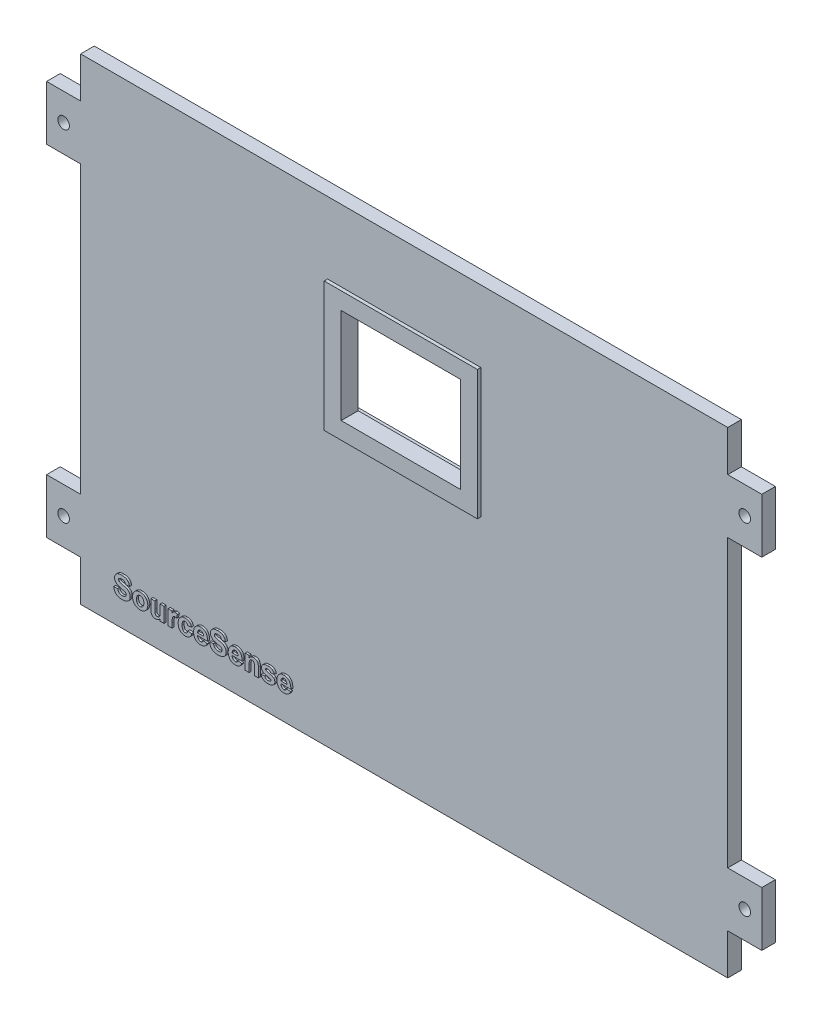
SolidWorks part; units mm, degrees
ref_plane "Front Plane" through (0, 0, 0) normal (0, 0, 1) x (1, 0, 0)
ref_plane "Top Plane" through (0, 0, 0) normal (0, 1, 0) x (1, 0, 0)
ref_plane "Right Plane" through (0, 0, 0) normal (1, 0, 0) x (0, 0, -1)
other "Configuration Table"
sketch "Sketch1" plane through (0, 0, 0) normal (0, 0, 1) x (1, 0, 0)
  line L0 (-95, -70) -> (95, -70)
  line L1 (95, -70) -> (95, 70)
  line L2 (95, 70) -> (-95, 70)
  line L3 (-95, 70) -> (-95, -70)
extrude "Lid_Plate" add sketch "Sketch1" along normal blind 4 from offset 44
sketch "Sketch2" plane through (0, 0, 0) normal (0, 0, 1) x (1, 0, 0)
  line L0 (-105, -58) -> (-95, -58)
  line L1 (-95, -58) -> (-95, -42)
  line L2 (-95, -42) -> (-105, -42)
  line L3 (-105, -42) -> (-105, -58)
  line L4 (-105, 42) -> (-95, 42)
  line L5 (-95, 42) -> (-95, 58)
  line L6 (-95, 58) -> (-105, 58)
  line L7 (-105, 58) -> (-105, 42)
  line L8 (95, -58) -> (105, -58)
  line L9 (105, -58) -> (105, -42)
  line L10 (105, -42) -> (95, -42)
  line L11 (95, -42) -> (95, -58)
  line L12 (95, 42) -> (105, 42)
  line L13 (105, 42) -> (105, 58)
  line L14 (105, 58) -> (95, 58)
  line L15 (95, 58) -> (95, 42)
extrude "Lid_Lugs" add sketch "Sketch2" along normal blind 4 from offset 44
sketch "Sketch3" plane through (0, 0, 0) normal (0, 0, 1) x (1, 0, 0)
  line L1 (-17.5, 16) -> (17.5, 16)
  line L2 (-17.5, 16) -> (-17.5, 44)
  line L3 (-17.5, 44) -> (17.5, 44)
  line L4 (17.5, 16) -> (17.5, 44)
  line L5 (-17.5, 16) -> (17.5, 44) construction
  line L6 (-17.5, 44) -> (17.5, 16) construction
  point P5 (0, 30)
  dimension "D1" = 35
  dimension "D2" = 28
extrude "TFT_Window" cut sketch "Sketch3" along normal through all and the other way through all
sketch "Sketch4" plane through (0, 0, 0) normal (0, 0, 1) x (1, 0, 0)
  line L0 (-22.5, 11) -> (22.5, 11)
  line L1 (22.5, 11) -> (22.5, 49)
  line L2 (22.5, 49) -> (-22.5, 49)
  line L3 (-22.5, 49) -> (-22.5, 11)
  line L4 (-17.5, 16) -> (17.5, 16)
  line L5 (17.5, 16) -> (17.5, 44)
  line L6 (17.5, 44) -> (-17.5, 44)
  line L7 (-17.5, 44) -> (-17.5, 16)
extrude "TFT_Bezel" add sketch "Sketch4" along normal blind 1 from offset 48
sketch "Sketch5" plane through (0, 0, 0) normal (0, 0, 1) x (1, 0, 0)
  circle A0 centre (-100, -50) radius 1.7
  circle A1 centre (-100, 50) radius 1.7
  circle A2 centre (100, -50) radius 1.7
  circle A3 centre (100, 50) radius 1.7
  dimension "D1" = 3.4
  dimension "D2" = 3.4
  dimension "D3" = 3.4
  dimension "D4" = 3.4
extrude "Lid_Screw_Holes_M3" cut sketch "Sketch5" along normal through all and the other way through all
sketch "Sketch6" plane through (0, 0, 0) normal (0, 0, 1) x (1, 0, 0)
  line L0 (-25, 10.2) -> (25, 10.2)
  line L1 (25, 10.2) -> (25, 12.2)
  line L2 (25, 12.2) -> (-25, 12.2)
  line L3 (-25, 12.2) -> (-25, 10.2)
  line L4 (-25, 47.8) -> (25, 47.8)
  line L5 (25, 47.8) -> (25, 49.8)
  line L6 (25, 49.8) -> (-25, 49.8)
  line L7 (-25, 49.8) -> (-25, 47.8)
extrude "TFT_Rails" add sketch "Sketch6" against normal blind 4.6 from offset 44
sketch "Sketch7" plane through (0, 0, 0) normal (0, 0, 1) x (1, 0, 0)
  text T0 "SourceSense" font "Arial" height 6
extrude "Label_SourceSense" add sketch "Sketch7" along normal blind 0.6 from offset 48
equation "\"Jar_OD\"= 90  'ASSUMED - Part G fallback - jar outer diameter"
equation "\"Jar_H\"= 120  'ASSUMED - Part G fallback - jar height"
equation "\"Pump_L\"= 45  'ASSUMED - Part G fallback"
equation "\"Pump_W\"= 24  'ASSUMED - Part G fallback"
equation "\"Pump_H\"= 33  'ASSUMED - Part G fallback"
equation "\"Pump_Outlet_OD\"= 7.5  'ASSUMED - Part G fallback"
equation "\"Tube_OD\"= 8  'ASSUMED - Part G fallback"
equation "\"Tube_ID\"= 6  'ASSUMED - Part G fallback"
equation "\"TDS_Body_Dia\"= 12  'ASSUMED - Part G fallback"
equation "\"TDS_Wet_Len\"= 45  'ASSUMED - Part G fallback - length in water"
equation "\"DS_Tube_Dia\"= 6  'ASSUMED - Part G fallback"
equation "\"DS_Tube_Len\"= 50  'ASSUMED - Part G fallback"
equation "\"ORP_Body_Dia\"= 12  'ASSUMED - Part G fallback"
equation "\"ORP_Body_Len\"= 150  'ASSUMED - Part G fallback"
equation "\"ORP_Cap_Dia\"= 16  'ASSUMED - Part G fallback"
equation "\"Turb_W\"= 33  'ASSUMED - Part G fallback - head width"
equation "\"Turb_D\"= 28  'ASSUMED - Part G fallback - head depth"
equation "\"Turb_H\"= 30  'ASSUMED - Part G fallback - head height"
equation "\"Turb_Slot_W\"= 10  'ASSUMED - Part G fallback - slot width"
equation "\"Flow_L\"= 62  'ASSUMED - Part G fallback YF-S201"
equation "\"Flow_W\"= 36  'ASSUMED - Part G fallback"
equation "\"Flow_H\"= 35  'ASSUMED - Part G fallback"
equation "\"Thread_G12_OD\"= 20.955  'ASSUMED - Part G fallback thread G1/2 (major diameter)"
equation "\"Valve_L\"= 75  'ASSUMED - Part G fallback"
equation "\"Valve_W\"= 45  'ASSUMED - Part G fallback"
equation "\"Valve_H\"= 60  'ASSUMED - Part G fallback"
equation "\"Tee_L\"= 40  'ASSUMED - Part G fallback - overall length"
equation "\"Tee_Branch_L\"= 25  'ASSUMED - Part G fallback"
equation "\"Tee_OD\"= 12  'ASSUMED - Part G fallback"
equation "\"LED_Board_L\"= 20  'ASSUMED - Part G fallback"
equation "\"LED_Board_W\"= 20  'ASSUMED - Part G fallback - LED at centre"
equation "\"GUVA_L\"= 20  'ASSUMED - Part G fallback"
equation "\"GUVA_W\"= 12  'ASSUMED - Part G fallback - sensor at centre"
equation "\"Reed_L\"= 27  'ASSUMED - Part G fallback MC-38 half"
equation "\"Reed_W\"= 14  'ASSUMED - Part G fallback"
equation "\"Reed_H\"= 8  'ASSUMED - Part G fallback"
equation "\"ESP_L\"= 51  'ASSUMED - Part G fallback"
equation "\"ESP_W\"= 28  'ASSUMED - Part G fallback"
equation "\"TFT_L\"= 58  'ASSUMED - Part G fallback - board"
equation "\"TFT_W\"= 35  'ASSUMED - Part G fallback - board"
equation "\"TFT_Win_L\"= 35  'ASSUMED - Part G fallback - visible window"
equation "\"TFT_Win_W\"= 28  'ASSUMED - Part G fallback - visible window"
equation "\"Relay_L\"= 50  'ASSUMED - Part G fallback"
equation "\"Relay_W\"= 26  'ASSUMED - Part G fallback"
equation "\"Relay_H\"= 19  'ASSUMED - Part G fallback"
equation "\"Mosfet_L\"= 34  'ASSUMED - Part G fallback"
equation "\"Mosfet_W\"= 17  'ASSUMED - Part G fallback"
equation "\"Mosfet_H\"= 12  'ASSUMED - Part G fallback"
equation "\"TDS_Board_L\"= 42  'ASSUMED - Part G fallback"
equation "\"TDS_Board_W\"= 32  'ASSUMED - Part G fallback"
equation "\"Turb_Board_L\"= 38  'ASSUMED - Part G fallback"
equation "\"Turb_Board_W\"= 28  'ASSUMED - Part G fallback"
equation "\"BNC_Thread_Dia\"= 9.5  'ASSUMED - Part G fallback"
equation "\"Plate_L\"= 420  'ASSUMED - Part G fallback"
equation "\"Plate_W\"= 297  'ASSUMED - Part G fallback"
equation "\"Plate_T\"= 6  'ASSUMED - Part G fallback"
equation "\"Booster_L\"= 150  'ASSUMED - Part G fallback - booster pump"
equation "\"Booster_W\"= 95  'ASSUMED - Part G fallback"
equation "\"Booster_H\"= 100  'ASSUMED - Part G fallback"
equation "\"PTube_OD\"= 6.35  'ASSUMED - Part G fallback - product tube 1/4 inch"
equation "\"Qz_Out\"= 12  'ASSUMED - Part G fallback - quartz channel outside square"
equation "\"Qz_Path\"= 10  'ASSUMED - Part G fallback - quartz channel inside light path"
equation "\"Qz_L\"= 40  'ASSUMED - Part G fallback - quartz channel length"
equation "\"LED860_Dia\"= 5  'ASSUMED - Part G fallback - 860 nm LED"
equation "\"BPW_L\"= 5.4  'ASSUMED - Part G fallback - BPW34"
equation "\"BPW_W\"= 4.3  'ASSUMED - Part G fallback - BPW34"
equation "\"Cart_Dia\"= 50  'ASSUMED - Part G fallback - sediment and pre-carbon cartridges"
equation "\"Cart_L\"= 255  'ASSUMED - Part G fallback"
equation "\"UF_Dia\"= 50  'ASSUMED - Part G fallback - UF cartridge"
equation "\"UF_L\"= 260  'ASSUMED - Part G fallback"
equation "\"RO_Dia\"= 62  'ASSUMED - Part G fallback - RO membrane housing"
equation "\"RO_L\"= 300  'ASSUMED - Part G fallback"
equation "\"UVC_Dia\"= 40  'ASSUMED - Part G fallback - UV-C chamber"
equation "\"UVC_L\"= 300  'ASSUMED - Part G fallback"
equation "\"Tank_W\"= 260  'ASSUMED - Part G fallback - storage tank"
equation "\"Tank_D\"= 160  'ASSUMED - Part G fallback"
equation "\"Tank_H\"= 300  'ASSUMED - Part G fallback"
equation "\"Cab_W\"= 400  'ASSUMED - Part G fallback - purifier cabinet"
equation "\"Cab_D\"= 270  'ASSUMED - Part G fallback"
equation "\"Cab_H\"= 560  'ASSUMED - Part G fallback"
equation "\"ORP_Board_L\"= 40  'ASSUMED - Part G fallback - ORP buffer board"
equation "\"ORP_Board_W\"= 30  'ASSUMED - Part G fallback"
equation "\"Opt_Board_L\"= 50  'ASSUMED - Part G fallback - optical front-end board"
equation "\"Opt_Board_W\"= 40  'ASSUMED - Part G fallback"
equation "\"Buck_L\"= 43  'ASSUMED - Part G fallback - 12 V to 5 V buck module"
equation "\"Buck_W\"= 21  'ASSUMED - Part G fallback"
equation "\"Buck_H\"= 14  'ASSUMED - Part G fallback"
equation "\"BB_L\"= 165  'ASSUMED - Part G fallback - breadboard (As_Built_R3 only)"
equation "\"BB_W\"= 55  'ASSUMED - Part G fallback"
equation "\"BB_H\"= 10  'ASSUMED - Part G fallback"
equation "\"Cuv_W\"= 12.5  'ASSUMED - old R3 cuvette (station suppressed in SS4)"
equation "\"Cuv_D\"= 12.5  'ASSUMED - old R3 cuvette (station suppressed in SS4)"
equation "\"Cuv_H\"= 45  'ASSUMED - old R3 cuvette (station suppressed in SS4)"
equation "\"Probe_Clr\"= 0.3  'DESIGN VALUE - Part C rule 3 - printed probe hole = diameter + 0.3"
equation "\"Label_H\"= 0.6  'DESIGN VALUE - Part D - raised label height"
equation "\"D1@Sketch3\" = \"TFT_Win_L\""
equation "\"D2@Sketch3\" = \"TFT_Win_W\""
equation "\"D1@Label_SourceSense\" = \"Label_H\""
